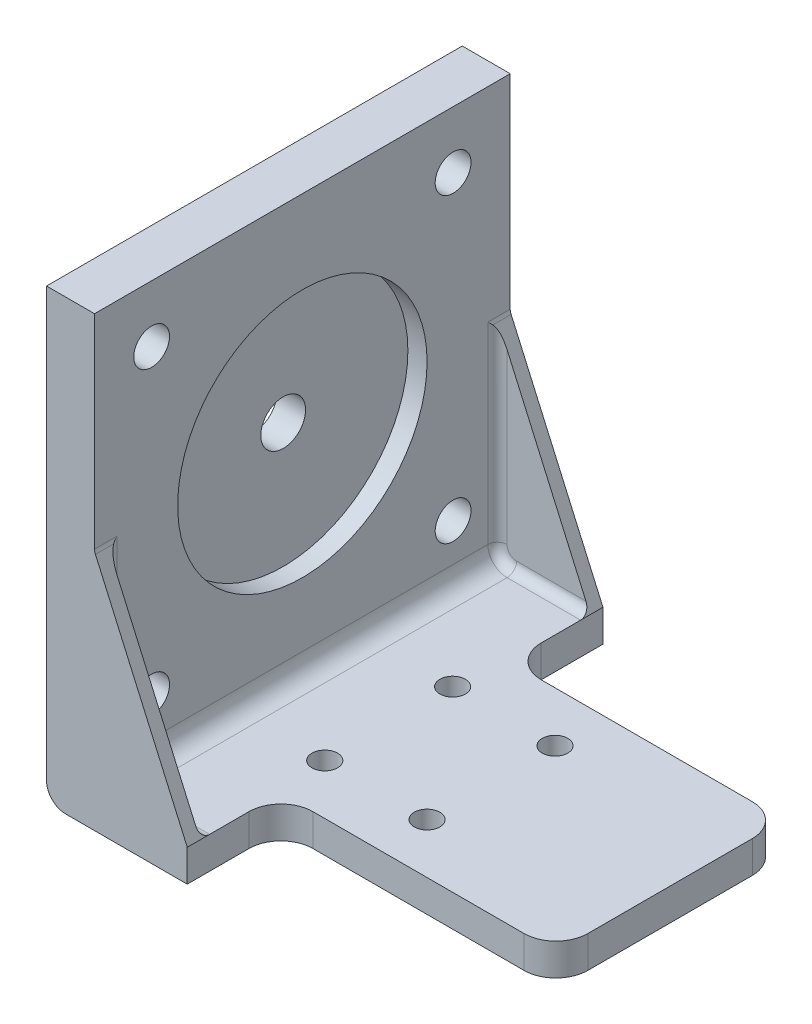
SolidWorks part; units mm, degrees
ref_plane "Front Plane" through (0, 0, 0) normal (0, 0, 1) x (1, 0, 0)
ref_plane "Top Plane" through (0, 0, 0) normal (0, 1, 0) x (1, 0, 0)
ref_plane "Right Plane" through (0, 0, 0) normal (1, 0, 0) x (0, 0, -1)
sketch "Sketch1" plane through (0, 0, 0) normal (0, 1, 0) x (1, 0, 0)
  line L5 (-32.5, 32.5) -> (27.5, 32.5)
  line L6 (-32.5, 32.5) -> (-32.5, -32.5)
  line L7 (-32.5, -32.5) -> (27.5, -32.5)
  line L8 (32.5, 27.5) -> (32.5, -27.5)
  line L9 (-32.5, 32.5) -> (32.5, -32.5) construction
  line L10 (-32.5, -32.5) -> (32.5, 32.5) construction
  arc A0 (27.5, -32.5) -> (32.5, -27.5) centre (27.5, -27.5) ccw
  arc A1 (27.5, 32.5) -> (32.5, 27.5) centre (27.5, 27.5) cw
  point P0 (0, 0)
  dimension "D3" = 5
  dimension "D1" = 65
  dimension "D2" = 65
extrude "Boss-Extrude1" add sketch "Sketch1" along normal blind 5
sketch "Sketch2" plane through (0, 5, 0) normal (0, 1, 0) x (1, 0, 0)
  line L0 (-32.5, -32.5) -> (27.5, -32.5) construction
  line L1 (-32.5, 32.5) -> (-25, 32.5)
  line L2 (-32.5, 32.5) -> (-32.5, -32.5)
  line L3 (-32.5, -32.5) -> (-25, -32.5)
  line L4 (-25, 32.5) -> (-25, -32.5)
  line L5 (27.5, 32.5) -> (-32.5, 32.5) construction
  dimension "D1" = 7.5
extrude "Boss-Extrude2" add sketch "Sketch2" along normal blind 65 contours L2 L1 L4 L3
fillet "Fillet2" radius 3 1 edges at (-32.5, 0, 0)
sketch "Sketch4" plane through (-25, 0, 0) normal (1, 0, 0) x (0, 0, -1)
  line L0 (0, 70) -> (0, 5) construction
  line L1 (32.5, 70) -> (-32.5, 70) construction
  line L2 (32.5, 5) -> (-32.5, 5) construction
  line L3 (-32.5, 37.5) -> (32.5, 37.5) construction
  line L4 (-32.5, 70) -> (-32.5, 5) construction
  line L5 (32.5, 70) -> (32.5, 5) construction
  circle A1 centre (0, 37.5) radius 19.5
  circle A2 centre (0, 37.5) radius 3.5
  circle A3 centre (-23.57, 61.07) radius 2.8
  circle A4 centre (23.57, 61.07) radius 2.8
  circle A5 centre (23.57, 13.93) radius 2.8
  circle A6 centre (-23.57, 13.93) radius 2.8
  dimension "D1" = 47.14
  dimension "D3" = 5.6
  dimension "D2" = 47.14
extrude "Cut-Extrude2" cut sketch "Sketch4" against normal through all contours A4 | A3 | A6 | A5 | A2
sketch "Sketch6" plane through (0, 5, 0) normal (0, 1, 0) x (1, 0, 0)
  line L0 (-14.5, 0) -> (27.1908, 0) construction
  line L2 (-32.5, 32.5) -> (-32.5, -32.5) construction
  circle A0 centre (4.5, -10) radius 2
  circle A1 centre (-11.5, -10) radius 2
  circle A2 centre (4.5, 10) radius 2
  circle A3 centre (-11.5, 10) radius 2
  point P9 (4.5, -10)
  point P10 (-11.5, -10)
  dimension "D1" = 21
  dimension "D2" = 16
  dimension "D3" = 10
extrude "Cut-Extrude3" cut sketch "Sketch6" against normal through all
sketch "Sketch7" plane through (-25, 0, 0) normal (1, 0, 0) x (0, 0, -1)
  circle A0 centre (0, 37.5) radius 19.5
extrude "Cut-Extrude4" cut sketch "Sketch7" against normal blind 3
sketch "Sketch8" plane through (-25, 0, 0) normal (1, 0, 0) x (0, 0, -1)
  line L1 (-32.5, 5) -> (-30.5, 5)
  line L2 (-32.5, 5) -> (-32.5, 37.5)
  line L3 (-32.5, 37.5) -> (-30.5, 37.5)
  line L4 (-30.5, 5) -> (-30.5, 37.5)
  line L6 (0, 70) -> (0, 5) construction
  line L7 (32.5, 70) -> (-32.5, 70) construction
  line L8 (-27.5, 5) -> (27.5, 5) construction
  line L9 (32.5, 5) -> (30.5, 5)
  line L10 (32.5, 5) -> (32.5, 37.5)
  line L11 (32.5, 37.5) -> (30.5, 37.5)
  line L12 (30.5, 5) -> (30.5, 37.5)
  dimension "D1" = 2
  dimension "D2" = 32.5
extrude "Boss-Extrude3" add sketch "Sketch8" along normal blind 32.5
sketch "Sketch9" plane through (0, 0, 32.5) normal (0, 0, 1) x (1, 0, 0)
  line L0 (-25, 37.5) -> (7.5, 5)
  line L1 (7.5, 5) -> (7.5, 37.5)
  line L2 (7.5, 37.5) -> (-25, 37.5)
extrude "Cut-Extrude5" cut sketch "Sketch9" against normal through all
fillet "Fillet3" radius 3 1 edges at (-25, 5, 0)
fillet "Fillet4" radius 1.5 10 edges at (-25, 22.75, -30.5) (-24.1213, 5.8787, -30.5) (-25, 22.75, 30.5) (-24.1213, 5.8787, 30.5) (-7.25, 5, -30.5) (-7.25, 5, 30.5) (7.5, 5, -31.5) (-25, 37.5, -31.5) (7.5, 5, 31.5) (-25, 37.5, 31.5)
sketch "Sketch10" plane through (0, 0, 0) normal (0, -1, 0) x (1, 0, 0)
  line L0 (-29.5, 0) -> (42.8579, 0) construction
  line L1 (-29.5, 32.5) -> (-29.5, -32.5) construction
  line L2 (-32.5, 0) -> (-28, 0) construction
  line L3 (-28, 0) -> (-25, 0) construction
  line L4 (32.5, 27.5) -> (32.5, -27.5) construction
  line L5 (-10.5, -17.85) -> (32.5, -17.85)
  line L7 (-10.5, 17.85) -> (32.5, 17.85)
  line L9 (-10.5, -17.85) -> (-10.5, -32.5)
  line L10 (27.5, -32.5) -> (-29.5, -32.5) construction
  line L11 (-10.5, -32.5) -> (27.5, -32.5)
  line L12 (32.5, -27.5) -> (32.5, -17.85)
  line L13 (-10.5, 17.85) -> (32.5, 17.85)
  line L14 (32.5, 27.5) -> (32.5, 17.85)
  line L15 (-10.5, 32.5) -> (27.5, 32.5)
  line L16 (-10.5, 17.85) -> (-10.5, 32.5)
  arc A0 (27.5, -32.5) -> (32.5, -27.5) centre (27.5, -27.5) ccw
  arc A1 (32.5, 27.5) -> (27.5, 32.5) centre (27.5, 27.5) ccw
  point P23 (32.5, -32.5)
  point P26 (32.5, 32.5)
  line M8 (27.5, 32.5) -> (-29.5, 32.5)
  line M10 (-29.5, -32.5) -> (27.5, -32.5)
  arc M11 (27.5, -32.5) -> (32.5, -27.5) centre (27.5, -27.5) ccw
  line M12 (32.5, -27.5) -> (32.5, 27.5)
  arc M13 (32.5, 27.5) -> (27.5, 32.5) centre (27.5, 27.5) ccw
  dimension "D3" = 5
  dimension "D1" = 35.7
  dimension "D2" = 43
extrude "Cut-Extrude6" cut sketch "Sketch10" against normal blind 5 contours L5 L9 M10 M11 M12 | L16 L7 M12 M13 M8
fillet "Fillet5" radius 5 4 edges at (-10.5, 2.5, 17.85) (-10.5, 2.5, -17.85) (32.5, 2.5, -17.85) (32.5, 2.5, 17.85)
sketch "Sketch12" plane through (0, 0, -32.5) normal (0, 0, -1) x (-1, 0, 0)
  line L0 (10.5, 5) -> (24.8858, 37.5473)
  line L1 (24.8858, 37.5473) -> (-8.1213, 5)
  arc A0 (24.5607, 37.0607) -> (25, 38.1213) centre (23.5, 38.1213) ccw construction
extrude "Cut-Extrude7" cut sketch "Sketch12" against normal through all and the other way through all
